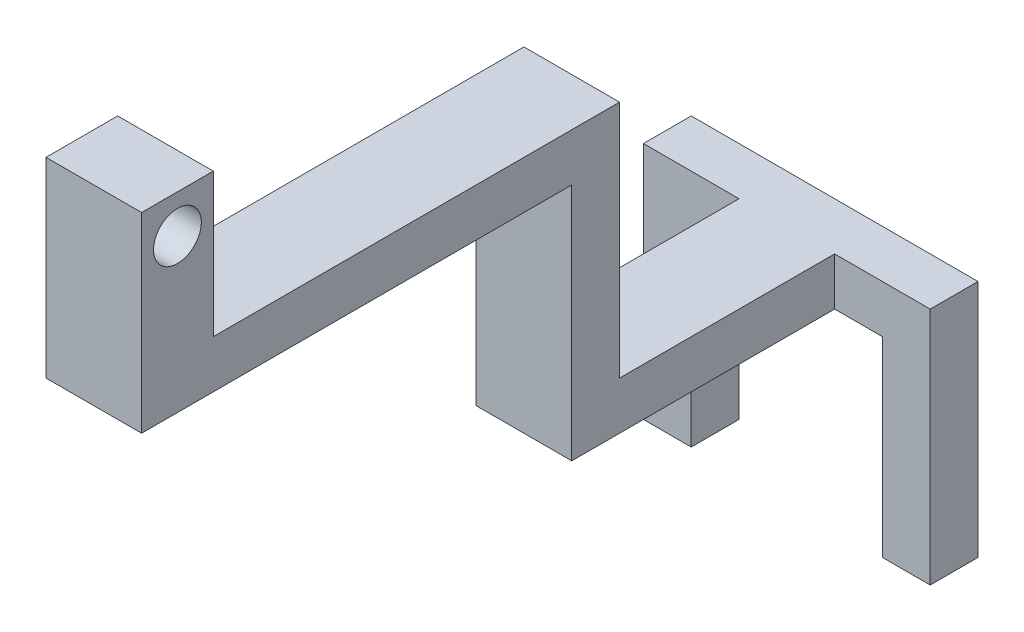
SolidWorks part; units mm, degrees
ref_plane "Přední rovina" through (0, 0, 0) normal (0, 0, 1) x (1, 0, 0)
ref_plane "Horní rovina" through (0, 0, 0) normal (0, 1, 0) x (1, 0, 0)
ref_plane "Pravá rovina" through (0, 0, 0) normal (1, 0, 0) x (0, 0, -1)
sketch "Skica1" plane through (0, 0, 0) normal (0, 0, 1) x (1, 0, 0)
  line L0 (0, 0) -> (60, 0)
  line L1 (60, 0) -> (60, -50)
  line L2 (60, -50) -> (50, -50)
  line L3 (50, -50) -> (50, -10)
  line L4 (50, -10) -> (10, -10)
  line L5 (10, -10) -> (10, -50)
  line L6 (10, -50) -> (0, -50)
  line L7 (0, -50) -> (0, 0)
  dimension "D1" = 60
  dimension "D2" = 40
  dimension "D3" = 10
  dimension "D4" = 10
  dimension "D5" = 40
  dimension "D6" = 40
  dimension "D7" = 10
extrude "Přidat vysunutím1" add sketch "Skica1" along normal blind 10
sketch "Skica2" plane through (0, 0, 10) normal (0, 0, 1) x (1, 0, 0)
  line L0 (60, 0) -> (0, 0) construction
  line L1 (20, 0) -> (40, 0)
  line L2 (20, 0) -> (20, -10)
  line L3 (20, -10) -> (40, -10)
  line L4 (40, 0) -> (40, -10)
  line L5 (10, -10) -> (50, -10) construction
  line L6 (0, 0) -> (0, -50) construction
  dimension "D1" = 20
  dimension "D2" = 20
extrude "Přidat vysunutím2" add sketch "Skica2" along normal blind 55
sketch "Skica4" plane through (0, 0, 0) normal (0, 1, 0) x (1, 0, 0)
  line L0 (40, -65) -> (40, -10) construction
  line L1 (20, -65) -> (40, -65)
  line L2 (20, -65) -> (20, -55)
  line L3 (20, -55) -> (40, -55)
  line L4 (40, -65) -> (40, -55)
  dimension "D1" = 10
extrude "Přidat vysunutím3" add sketch "Skica4" along normal blind 50
sketch "Skica5" plane through (0, 0, 65) normal (0, 0, 1) x (1, 0, 0)
  line L0 (40, -10) -> (40, 50) construction
  line L1 (20, 50) -> (40, 50)
  line L2 (20, 50) -> (20, 40)
  line L3 (20, 40) -> (40, 40)
  line L4 (40, 50) -> (40, 40)
  dimension "D1" = 10
extrude "Přidat vysunutím4" add sketch "Skica5" along normal blind 90
sketch "Skica6" plane through (0, 50, 0) normal (0, 1, 0) x (1, 0, 0)
  line L0 (40, -155) -> (40, -55) construction
  line L1 (20, -155) -> (40, -155)
  line L2 (20, -155) -> (20, -140)
  line L3 (20, -140) -> (40, -140)
  line L4 (40, -155) -> (40, -140)
  dimension "D1" = 15
extrude "Přidat vysunutím5" add sketch "Skica6" along normal blind 30
sketch "Skica7" plane through (40, 0, 0) normal (1, 0, 0) x (0, 0, -1)
  line L0 (-140, 80) -> (-140, 50) construction
  line L1 (-155, 80) -> (-140, 80) construction
  circle A0 centre (-147.5, 72) radius 5
  dimension "D1" = 10
  dimension "D2" = 7.5
  dimension "D3" = 8
extrude "Odebrat vysunutím1" cut sketch "Skica7" against normal blind 20
